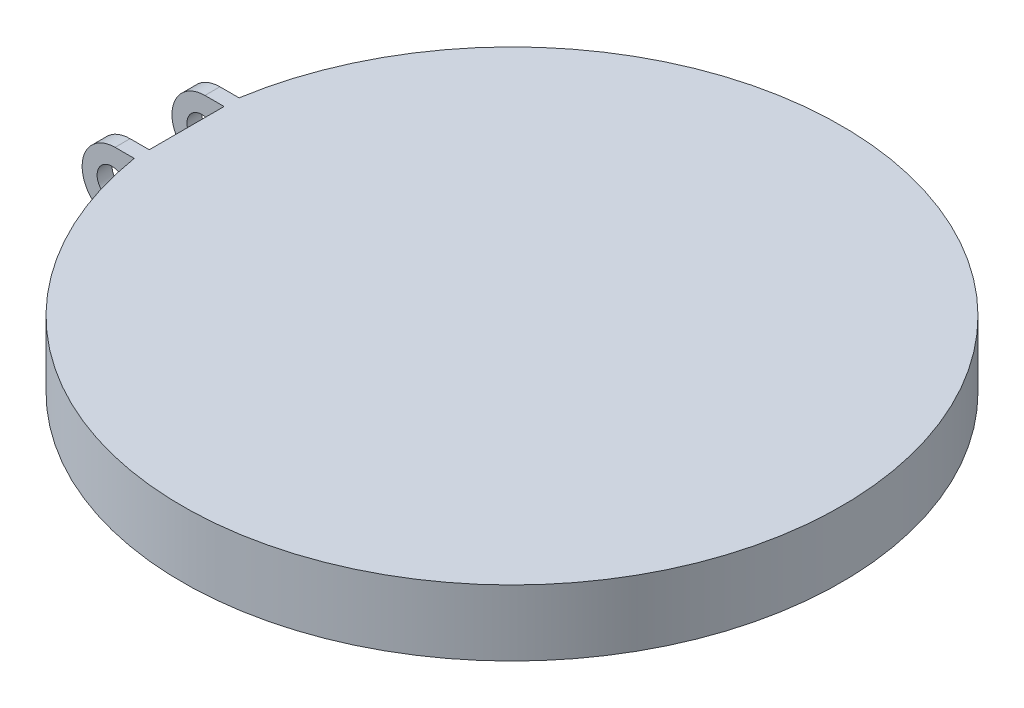
SolidWorks part; units mm, degrees
material "1023 Carbon Steel Sheet (SS)"
ref_plane "Front Plane" through (0, 0, 0) normal (0, 0, 1) x (1, 0, 0)
ref_plane "Top Plane" through (0, 0, 0) normal (0, 1, 0) x (1, 0, 0)
ref_plane "Right Plane" through (0, 0, 0) normal (1, 0, 0) x (0, 0, -1)
sketch "Sketch2" plane through (0, 0, 0) normal (0, 0, 1) x (1, 0, 0)
  line L0 (0, 0) -> (0, 5.588)
  line L1 (0, 5.588) -> (27.94, 5.588)
  line L2 (27.94, 5.588) -> (27.94, 0)
  line L3 (27.94, 0) -> (24.638, 0)
  line L4 (24.638, 0) -> (24.638, -1.27)
  line L5 (24.638, -1.27) -> (23.368, -1.27)
  line L6 (23.368, -1.27) -> (23.368, 0)
  line L7 (23.368, 0) -> (0, 0)
  line L8 (0, -1000) -> (0, 49000) construction
  dimension "D1" = 1.27
  dimension "D3" = 5.588
  dimension "D4" = 23.368
  dimension "D5" = 1.27
revolve "Revolve1" add sketch "Sketch2" angle 360 about L8
sketch "Sketch3" plane through (0, 0, 0) normal (0, 0, 1) x (1, 0, 0)
  line L0 (0, 0) -> (-29.21, 0) construction
  line L1 (0, 0) -> (0, 5.588) construction
  line L2 (27.94, 5.588) -> (-27.94, 5.588) construction
  line L3 (0, 2.794) -> (-29.464, 2.794) construction
  line L5 (-29.21, 0) -> (-27.305, 0)
  line L6 (-27.305, 0) -> (-27.305, 5.588)
  line L7 (-27.305, 5.588) -> (-29.21, 5.588)
  circle A0 centre (-29.464, 2.794) radius 1.27
  arc A1 (-29.21, 5.588) -> (-29.21, 0) centre (-29.21, 2.794) ccw
  point P13 (0, 0)
  dimension "D3" = 2.54
  dimension "D1" = 29.21
  dimension "D2" = 27.305
  dimension "D4" = 29.464
extrude "Boss-Extrude1" add sketch "Sketch3" along normal mid plane 8.89
sketch "Sketch4" plane through (0, 5.588, 0) normal (0, 1, 0) x (1, 0, 0)
  line L0 (-27.5842, 4.445) -> (-27.5842, -4.445) construction
  line L1 (-27.5842, -4.445) -> (-29.21, -4.445) construction
  line L2 (-32.004, 3.175) -> (-27.5842, 3.175) construction
  line L3 (-32.004, 4.445) -> (-32.004, -4.445) construction
  line L4 (-32.004, -3.175) -> (-27.5842, -3.175) construction
  line L5 (-32.004, 3.175) -> (-32.004, -3.175)
  line L6 (-32.004, -3.175) -> (-27.5842, -3.175)
  line L7 (-27.5842, -3.175) -> (-27.5842, 3.175)
  line L8 (-27.5842, 3.175) -> (-32.004, 3.175)
  circle A0 centre (0, 0) radius 27.94 construction
  dimension "D1" = 1.27
  dimension "D2" = 1.27
extrude "Cut-Extrude1" cut sketch "Sketch4" against normal up to surface (5.588 mm away) up to face at (-14.516, 0, 0)
